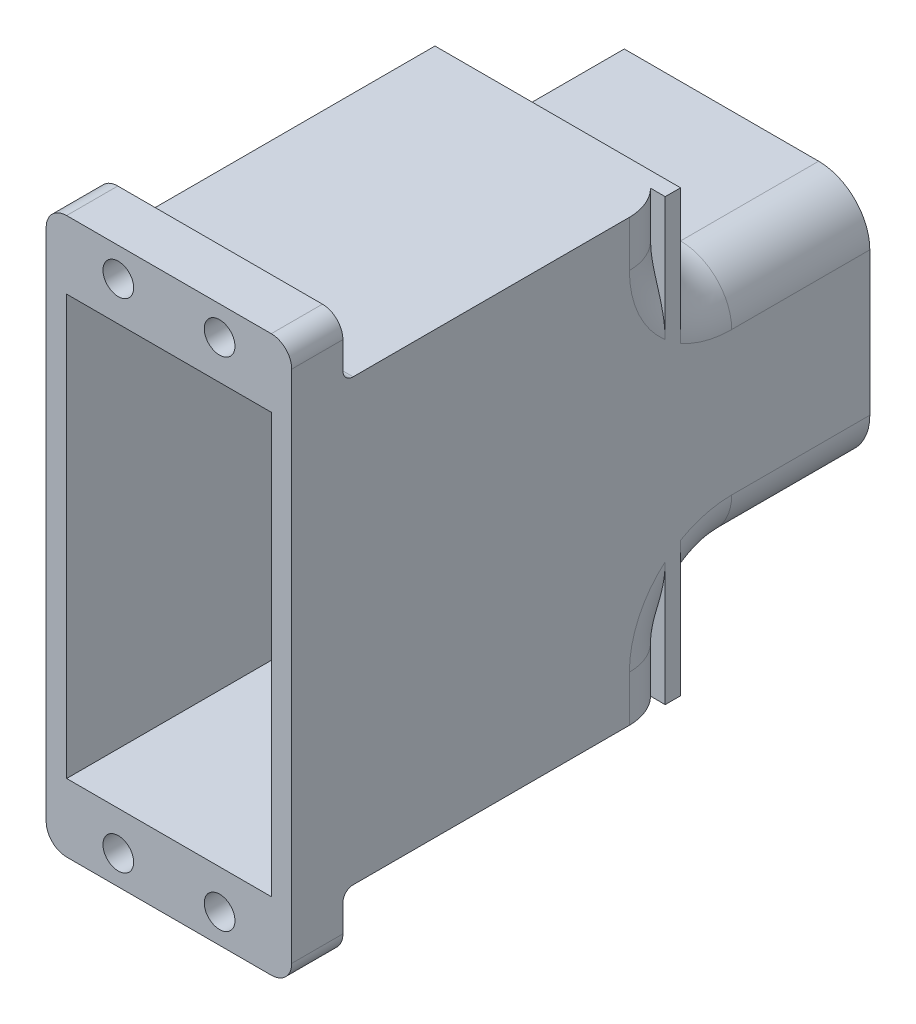
SolidWorks part; units mm, degrees
ref_plane "前视基准面" through (0, 0, 0) normal (0, 0, 1) x (1, 0, 0)
ref_plane "上视基准面" through (0, 0, 0) normal (0, 1, 0) x (1, 0, 0)
ref_plane "右视基准面" through (0, 0, 0) normal (1, 0, 0) x (0, 0, -1)
sketch "草图1" plane through (0, 0, 0) normal (0, 0, 1) x (1, 0, 0)
  line L1 (-12, 12) -> (12, 12)
  line L2 (-12, 12) -> (-12, -12)
  line L3 (-12, -12) -> (12, -12)
  line L4 (12, 12) -> (12, -12)
  line L5 (0, -12) -> (0, 12) construction
  line L6 (-12, 0) -> (12, 0) construction
  point P0 (0, 0)
  dimension "D1" = 24
extrude "凸台-拉伸1" add sketch "草图1" along normal blind 30
sketch "草图2" plane through (0, 0, 0) normal (0, 0, -1) x (-1, 0, 0)
  line L1 (-10.5, 10.5) -> (10.5, 10.5)
  line L2 (-10.5, 10.5) -> (-10.5, -10.5)
  line L3 (-10.5, -10.5) -> (10.5, -10.5)
  line L4 (10.5, 10.5) -> (10.5, -10.5)
  line L5 (0, -10.5) -> (0, 10.5) construction
  line L6 (-10.5, 0) -> (10.5, 0) construction
  point P0 (0, 0)
  dimension "D1" = 21
extrude "切除-拉伸1" cut sketch "草图2" against normal through all
sketch "草图3" plane through (0, 0, 30) normal (0, 0, 1) x (1, 0, 0)
  line L0 (-12, -12) -> (12, -12) construction
  line L5 (-12, 12) -> (-7, 12)
  line L6 (-12, 12) -> (-12, -12)
  line L7 (-12, -12) -> (-7, -12)
  line L8 (-7, 12) -> (-7, -12)
  dimension "D1" = 5
extrude "凸台-拉伸3" add sketch "草图3" along normal blind 2
sketch "草图4" plane through (0, 0, 30) normal (0, 0, 1) x (1, 0, 0)
  line L0 (-7, -12) -> (-7, 12) construction
  line L1 (12, -12) -> (-7, -12)
  line L2 (12, -12) -> (12, -7)
  line L3 (12, -7) -> (-7, -7)
  line L4 (-7, -12) -> (-7, -7)
  dimension "D1" = 5
extrude "凸台-拉伸4" add sketch "草图4" along normal blind 2
sketch "草图5" plane through (0, 0, 30) normal (0, 0, 1) x (1, 0, 0)
  line L0 (12, 12) -> (-7, 12) construction
  line L1 (12, -7) -> (7, -7)
  line L2 (12, -7) -> (12, 12)
  line L3 (12, 12) -> (7, 12)
  line L4 (7, -7) -> (7, 12)
  dimension "D1" = 5
extrude "凸台-拉伸5" add sketch "草图5" along normal blind 2
sketch "草图6" plane through (0, 0, 30) normal (0, 0, 1) x (1, 0, 0)
  line L0 (7, 12) -> (7, -7) construction
  line L1 (-7, 12) -> (7, 12)
  line L2 (-7, 12) -> (-7, 7)
  line L3 (-7, 7) -> (7, 7)
  line L4 (7, 12) -> (7, 7)
  dimension "D1" = 5
extrude "凸台-拉伸6" add sketch "草图6" along normal blind 2
sketch "草图7" plane through (0, 0, 32) normal (0, 0, 1) x (1, 0, 0)
  line L0 (12, -12) -> (12, 12) construction
  line L1 (-12, 21.5) -> (12, 21.5)
  line L2 (-12, 21.5) -> (-12, -21.5)
  line L3 (-12, -21.5) -> (12, -21.5)
  line L4 (12, 21.5) -> (12, -21.5)
  line L5 (0, -21.5) -> (0, 21.5) construction
  line L6 (-12, 0) -> (12, 0) construction
  point P0 (0, 0)
  dimension "D2" = 43
extrude "凸台-拉伸7" add sketch "草图7" along normal blind 28
sketch "草图9" plane through (0, 0, 60) normal (0, 0, 1) x (1, 0, 0)
  line L1 (-10, 20.5) -> (10, 20.5)
  line L2 (-10, 20.5) -> (-10, -20.5)
  line L3 (-10, -20.5) -> (10, -20.5)
  line L4 (10, 20.5) -> (10, -20.5)
  line L5 (0, -20.5) -> (0, 20.5) construction
  line L6 (-10, 0) -> (10, 0) construction
  point P0 (0, 0)
  dimension "D1" = 41
  dimension "D2" = 20
extrude "切除-拉伸2" cut sketch "草图9" against normal blind 27
sketch "草图10" plane through (0, 0, 60) normal (0, 0, 1) x (1, 0, 0)
  point P0 (0, 0)
sketch "草图11" plane through (0, 0, 60) normal (0, 0, 1) x (1, 0, 0)
  line L0 (12, -21.5) -> (12, 21.5) construction
  line L1 (-12, 27.15) -> (12, 27.15)
  line L2 (-12, 27.15) -> (-12, -27.15)
  line L3 (-12, -27.15) -> (12, -27.15)
  line L4 (12, 27.15) -> (12, -27.15)
  line L5 (0, -27.15) -> (0, 27.15) construction
  line L6 (-12, 0) -> (12, 0) construction
  point P0 (0, 0)
  dimension "D1" = 54.3
extrude "凸台-拉伸20" add sketch "草图11" along normal blind 10
sketch "草图12" plane through (0, 0, 70) normal (0, 0, 1) x (1, 0, 0)
  line L6 (-10, 20.5) -> (10, 20.5)
  line L7 (-10, 20.5) -> (-10, -20.5)
  line L8 (-10, -20.5) -> (10, -20.5)
  line L9 (10, 20.5) -> (10, -20.5)
  line L10 (0, -20.5) -> (0, 20.5) construction
  line L11 (-10, 0) -> (10, 0) construction
  point P0 (0, 0)
  point P1 (0, 0)
  dimension "D1" = 20
  dimension "D2" = 41
extrude "切除-拉伸4" cut sketch "草图12" against normal blind 10
sketch "草图13" plane through (0, 0, 70) normal (0, 0, 1) x (1, 0, 0)
  line L0 (-23.1116, 0) -> (28.6646, 0) construction
  line L1 (0, 27.7787) -> (0, -31.2712) construction
  circle A0 centre (-4.95, -24.3104) radius 1.5
  circle A1 centre (4.95, -24.3104) radius 1.5
  circle A2 centre (4.95, 24.3104) radius 1.5
  circle A3 centre (-4.95, 24.3104) radius 1.5
  dimension "D1" = 3
  dimension "D2" = 3
  dimension "D3" = 4.95
  dimension "D4" = 4.95
extrude "切除-拉伸5" cut sketch "草图13" against normal blind 10
fillet "圆角2" radius 5 2 edges at (0, -12, 32) (0, 12, 32)
fillet "圆角3" radius 2 4 edges at (12, -27.15, 65) (-12, -27.15, 65) (-12, 27.15, 65) (12, 27.15, 65)
sketch "草图15" plane through (0, 0, 60) normal (0, 0, -1) x (-1, 0, 0)
  line L4 (-12, -21.5) -> (-12, -25.15)
  line L5 (-10, -27.15) -> (10, -27.15)
  line L6 (12, -25.15) -> (12, -21.5)
  line L7 (12, -21.5) -> (-12, -21.5)
  line L8 (-12, -21.5) -> (-12, -25.15)
  line L9 (-10, -27.15) -> (10, -27.15)
  line L10 (12, -25.15) -> (12, -21.5)
  line L11 (12, -21.5) -> (-12, -21.5)
  arc A2 (-12, -25.15) -> (-10, -27.15) centre (-10, -25.15) ccw
  arc A3 (10, -27.15) -> (12, -25.15) centre (10, -25.15) ccw
  arc A4 (-12, -25.15) -> (-10, -27.15) centre (-10, -25.15) ccw
  arc A5 (10, -27.15) -> (12, -25.15) centre (10, -25.15) ccw
  dimension "D1" = 0
extrude "切除-拉伸6" cut sketch "草图15" against normal blind 5
sketch "草图16" plane through (0, 0, 60) normal (0, 0, -1) x (-1, 0, 0)
  line L4 (12, 21.5) -> (12, 25.15)
  line L5 (10, 27.15) -> (-10, 27.15)
  line L6 (-12, 25.15) -> (-12, 21.5)
  line L7 (-12, 21.5) -> (12, 21.5)
  line L8 (12, 21.5) -> (12, 25.15)
  line L9 (10, 27.15) -> (-10, 27.15)
  line L10 (-12, 25.15) -> (-12, 21.5)
  line L11 (-12, 21.5) -> (12, 21.5)
  arc A2 (12, 25.15) -> (10, 27.15) centre (10, 25.15) ccw
  arc A3 (-10, 27.15) -> (-12, 25.15) centre (-10, 25.15) ccw
  arc A4 (12, 25.15) -> (10, 27.15) centre (10, 25.15) ccw
  arc A5 (-10, 27.15) -> (-12, 25.15) centre (-10, 25.15) ccw
  dimension "D1" = 0
extrude "切除-拉伸7" cut sketch "草图16" against normal blind 5
fillet "圆角4" radius 1 2 edges at (0, -21.5, 65) (0, 21.5, 65)
sketch "草图17" plane through (-12, 0, 0) normal (-1, 0, 0) x (0, 0, 1)
  line L0 (27, -12) -> (0, -12) construction
  line L1 (0, 12.1009) -> (13.5, 12.1009)
  line L2 (0, 12.1009) -> (0, -12)
  line L3 (0, -12) -> (13.5, -12)
  line L4 (13.5, 12.1009) -> (13.5, -12)
extrude "切除-拉伸8" cut sketch "草图17" against normal blind 45
fillet "圆角6" radius 5 6 edges at (12, 12, 20.25) (12, -12, 20.25) (12, 19.25, 32) (12, 13.4645, 30.5355) (12, -19.25, 32) (12, -13.4645, 30.5355)
sketch "草图27" plane through (0, 0, 32) normal (0, 0, -1) x (-1, 0, 0)
  line L6 (-12, 17) -> (-12, 3.0594)
  line L8 (-12, -21.5) -> (12, -21.5)
  line L9 (12, -21.5) -> (12, 21.5)
  line L10 (12, 21.5) -> (-12, 21.5)
  line L11 (-12, 21.5) -> (-12, 17)
  line L15 (-12, 17) -> (-12, 3.0594)
  line L16 (-12, -21.5) -> (12, -21.5)
  line L17 (12, -21.5) -> (12, 21.5)
  line L18 (12, 21.5) -> (-12, 21.5)
  line L19 (-12, 21.5) -> (-12, 17)
  line L30 (-12, 3.0594) -> (-12, -3.0594)
  line L31 (-12, 3.0594) -> (-12, -3.0594)
  line L32 (-12, -3.0594) -> (-12, -17)
  line L33 (-12, -3.0594) -> (-12, -17)
  line L34 (-12, -17) -> (-12, -21.5)
  line L35 (-12, -17) -> (-12, -21.5)
  dimension "D1" = 0
extrude "凸台-拉伸23" add sketch "草图27" along normal up to surface (1.5 mm away)
